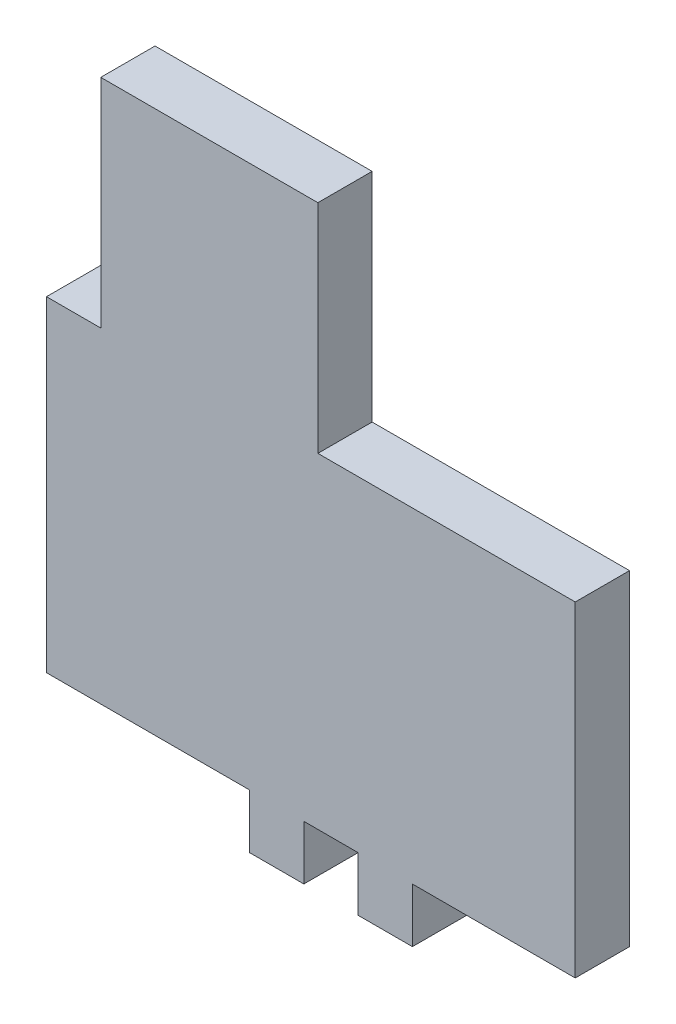
SolidWorks part; units mm, degrees
ref_plane "Plan de face" through (0, 0, 0) normal (0, 0, 1) x (1, 0, 0)
ref_plane "Plan de dessus" through (0, 0, 0) normal (0, 1, 0) x (1, 0, 0)
ref_plane "Plan de droite" through (0, 0, 0) normal (1, 0, 0) x (0, 0, -1)
sketch "Esquisse1" plane through (0, 0, 0) normal (0, 0, 1) x (1, 0, 0)
  line L0 (-76.6518, 2.6702) -> (-71.6518, 2.6702)
  line L1 (-71.6518, 2.6702) -> (-71.6518, 22.6702)
  line L2 (-76.6518, 2.6702) -> (-76.6518, -27.3298)
  line L3 (-71.6518, 22.6702) -> (-51.6518, 22.6702)
  line L20 (-76.6518, -27.3298) -> (-57.9418, -27.3298)
  line L21 (-57.9418, -27.3298) -> (-57.9418, -32.3298)
  line L22 (-57.9418, -32.3298) -> (-52.9418, -32.3298)
  line L23 (-52.9418, -32.3298) -> (-52.9418, -27.3298)
  line L24 (-52.9418, -27.3298) -> (-47.9418, -27.3298)
  line L25 (-47.9418, -27.3298) -> (-47.9418, -32.3298)
  line L26 (-47.9418, -32.3298) -> (-42.9418, -32.3298)
  line L27 (-42.9418, -32.3298) -> (-42.9418, -27.3298)
  line L28 (-42.9418, -27.3298) -> (-27.9418, -27.3298)
  line L29 (-27.9418, -27.3298) -> (-27.9418, 2.6702)
  line L30 (-27.9418, 2.6702) -> (-51.6518, 2.6702)
  line L31 (-51.6518, 2.6702) -> (-51.6518, 22.6702)
  dimension "D1" = 18.71
  dimension "D2" = 15
  dimension "D3" = 5
  dimension "D4" = 5
  dimension "D5" = 30
  dimension "D6" = 20
  dimension "D7" = 25
  dimension "D8" = 5
extrude "Boss.-Extru.1" add sketch "Esquisse1" along normal blind 5
